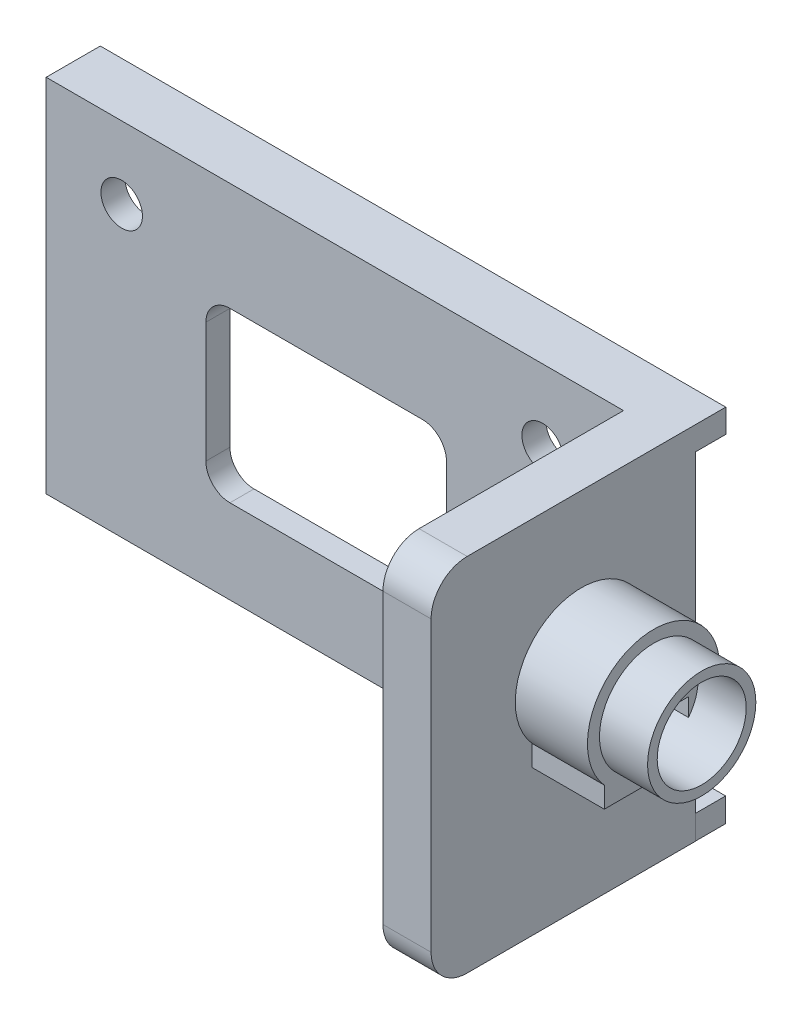
SolidWorks part; units mm, degrees
ref_plane "Front Plane" through (0, 0, 0) normal (0, 0, 1) x (1, 0, 0)
ref_plane "Top Plane" through (0, 0, 0) normal (0, 1, 0) x (1, 0, 0)
ref_plane "Right Plane" through (0, 0, 0) normal (1, 0, 0) x (0, 0, -1)
sketch "Sketch1" plane through (0, 0, 0) normal (0, 0, 1) x (1, 0, 0)
  line L1 (0, 0) -> (52, 0)
  line L2 (0, 0) -> (0, -30)
  line L3 (0, -30) -> (52, -30)
  line L4 (52, 0) -> (52, -30)
  dimension "D1" = 52
  dimension "D2" = 30
extrude "Boss-Extrude1" add sketch "Sketch1" along normal blind 2
ref_plane "Plane1" through (0, 0, 2) normal (0, 0, -1) x (-1, 0, 0)
sketch "Sketch2" plane through (0, 0, 2) normal (0, 0, -1) x (-1, 0, 0)
  line L1 (-48, 0) -> (-52, 0)
  line L2 (-48, 0) -> (-48, -30)
  line L3 (-48, -30) -> (-52, -30)
  line L4 (-52, 0) -> (-52, -30)
  dimension "D1" = 4
extrude "Boss-Extrude2" add sketch "Sketch2" against normal blind 20
fillet "Fillet1" radius 3 2 edges at (50, -30, 22) (50, 0, 22)
sketch "Sketch4" plane through (0, 0, 2) normal (0, 0, 1) x (1, 0, 0)
  line L0 (48, 0) -> (0, 0) construction
  circle A0 centre (41.2777, -6) radius 1.725
  circle A1 centre (6.2777, -6) radius 1.725
  dimension "D1" = 35
  dimension "D2" = 6
  dimension "D3" = 6
extrude "Cut-Extrude2" cut sketch "Sketch4" against normal up to surface (2 mm away) up to face at (26, -15, 0)
sketch "Sketch5" plane through (0, 0, 0) normal (0, 0, -1) x (-1, 0, 0)
  line L0 (0, -15) -> (10.3678, -15) construction
  line L5 (0, 0) -> (0, -30) construction
  line L6 (0, 0) -> (0, -30) construction
  line L7 (-51.9884, -30) -> (0, -30)
  line L8 (-51.9884, -30) -> (-51.9884, -28)
  line L9 (-51.9884, -28) -> (0, -28)
  line L10 (0, -30) -> (0, -28)
  line L12 (-52, -1.966) -> (0, -2.1935)
  line L13 (0, 0) -> (0, -2.1935)
  line L14 (-52, 0) -> (0, 0)
  line L15 (-52, 0) -> (-52, -1.966)
  dimension "D1" = 2
extrude "Boss-Extrude3" add sketch "Sketch5" along normal blind 2.5
sketch "Sketch6" plane through (0, 0, 2) normal (0, 0, 1) x (1, 0, 0)
  line L0 (48, 0) -> (0, 0) construction
  line L1 (33.2777, -9) -> (13.2777, -9)
  line L2 (33.2777, -9) -> (33.2777, -23)
  line L3 (33.2777, -23) -> (13.2777, -23)
  line L4 (13.2777, -9) -> (13.2777, -23)
  circle A0 centre (6.2777, -6) radius 1.725 construction
  dimension "D3" = 7
  dimension "D1" = 14
  dimension "D2" = 20
  dimension "D4" = 9
extrude "Cut-Extrude3" cut sketch "Sketch6" against normal up to surface (2 mm away) up to face at (43.0027, -6, 0)
sketch "Sketch7" plane through (52, 0, 0) normal (1, 0, 0) x (0, 0, -1)
  line L0 (-22, -15) -> (2.0181, -15) construction
  line L1 (-12.4, -16.7) -> (-6.6, -16.7)
  line L2 (-12.4, -16.7) -> (-12.4, -13.3)
  line L3 (-12.4, -13.3) -> (-6.6, -13.3)
  line L4 (-6.6, -16.7) -> (-6.6, -13.3)
  line L5 (-22, -3) -> (-22, -27) construction
  line L6 (-9.5, -30) -> (-9.5, 5.4647) construction
  line L7 (-19, -30) -> (0, -30) construction
  line L8 (-13.6, -12.1) -> (-5.4, -12.1)
  line L9 (-5.4, -17.9) -> (-5.4, -12.1)
  line L10 (-13.6, -17.9) -> (-5.4, -17.9)
  line L11 (-13.6, -17.9) -> (-13.6, -12.1)
  dimension "D5" = 1.2
  dimension "D1" = 5.8
  dimension "D2" = 3.4
  dimension "D3" = 1.7
  dimension "D4" = 2.9
sketch "Sketch8" plane through (52, 0, 0) normal (1, 0, 0) x (0, 0, -1)
  line L0 (-9.5, -12.5) -> (-9.5, 10.2333) construction
  circle A0 centre (-9.5, -12.5) radius 4.25
  circle A1 centre (-9.5, -12.5) radius 5.5
extrude "Boss-Extrude4" add sketch "Sketch7" along normal blind 6
extrude "Boss-Extrude5" add sketch "Sketch8" along normal blind 6
sketch "Sketch10" plane through (52, 0, 0) normal (1, 0, 0) x (0, 0, -1)
  line L0 (-9.5, -14.2) -> (-9.5, 2.6372) construction
  line L2 (-12.4, -12.5) -> (-2.926, -12.5) construction
  circle A0 centre (-9.5, -12.5) radius 4.5
  circle A1 centre (-9.5, -12.5) radius 3.7
extrude "Boss-Extrude6" add sketch "Sketch10" along normal blind 10
fillet "Fillet2" radius 2 4 edges at (13.2777, -9, 1) (13.2777, -23, 1) (33.2777, -9, 1) (33.2777, -23, 1)
